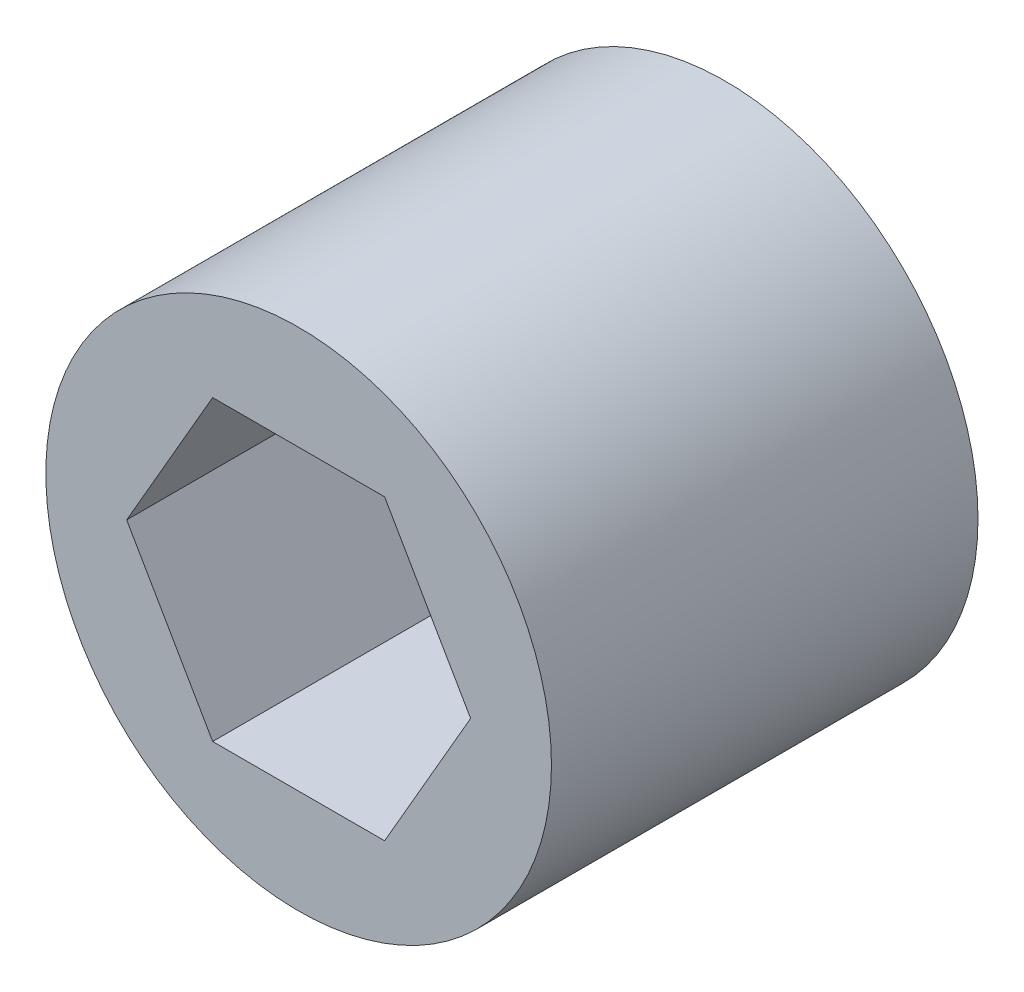
SolidWorks part; units mm, degrees
material "ABS"
ref_plane "Front" through (0, 0, 0) normal (0, 0, 1) x (1, 0, 0)
ref_plane "Top" through (0, 0, 0) normal (0, 1, 0) x (1, 0, 0)
ref_plane "Right" through (0, 0, 0) normal (1, 0, 0) x (0, 0, -1)
sketch "Sketch1" plane through (0, 0, 0) normal (0, 0, 1) x (1, 0, 0)
  line L1 (5.9392, 0) -> (2.9696, 5.1435)
  line L2 (2.9696, 5.1435) -> (-2.9696, 5.1435)
  line L3 (-2.9696, 5.1435) -> (-5.9392, 0)
  line L4 (-5.9392, 0) -> (-2.9696, -5.1435)
  line L5 (-2.9696, -5.1435) -> (2.9696, -5.1435)
  line L6 (2.9696, -5.1435) -> (5.9392, 0)
  circle A0 centre (0, 0) radius 5.1435 construction
  circle A1 centre (0, 0) radius 8.7312
  dimension "D1" = 10.287
  dimension "D2" = 17.4625
extrude "Boss-Extrude1" add sketch "Sketch1" along normal blind 14.732
